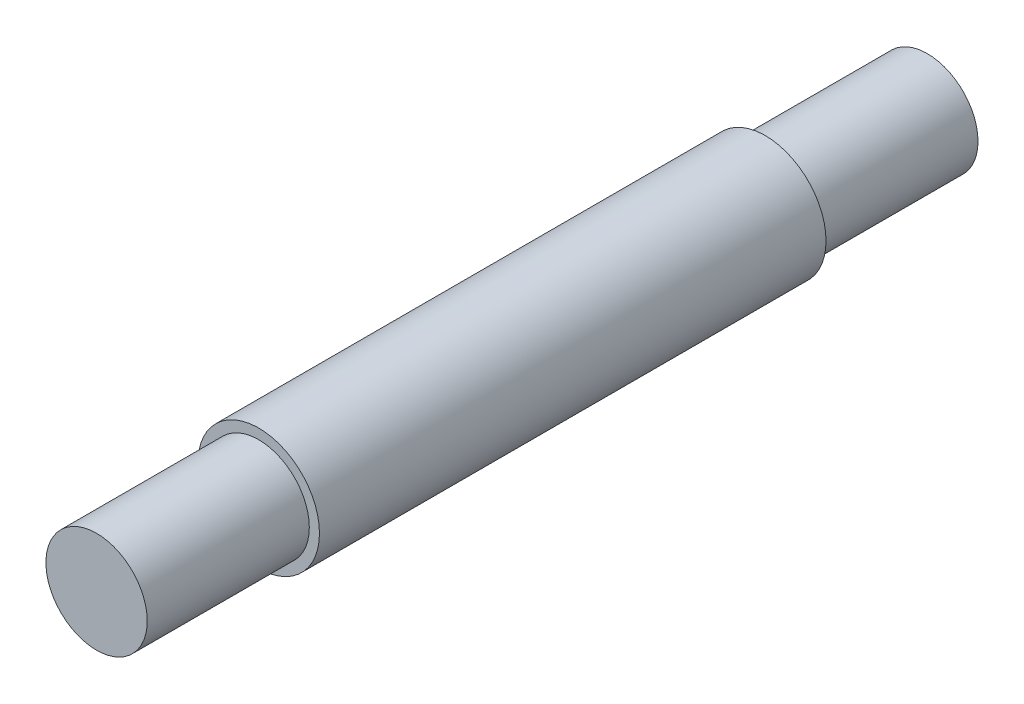
SolidWorks part; units mm, degrees
ref_plane "Ön Düzlem" through (0, 0, 0) normal (0, 0, 1) x (1, 0, 0)
ref_plane "Üst Düzlem" through (0, 0, 0) normal (0, 1, 0) x (1, 0, 0)
ref_plane "Sağ Düzlem" through (0, 0, 0) normal (1, 0, 0) x (0, 0, -1)
sketch "Sketch1" plane through (0, 0, 0) normal (0, 0, 1) x (1, 0, 0)
  circle A0 centre (0, 0) radius 5
  dimension "D1" = 10
extrude "Boss-Extrude1" add sketch "Sketch1" along normal blind 82
ref_plane "Plane2" through (0, 0, 66) normal (0, 0, 1) x (1, 0, 0)
sketch "Sketch2" plane through (0, 0, 66) normal (0, 0, 1) x (1, 0, 0)
  circle A0 centre (0, 0) radius 6
  dimension "D1" = 12
extrude "Boss-Extrude2" add sketch "Sketch2" against normal blind 50
